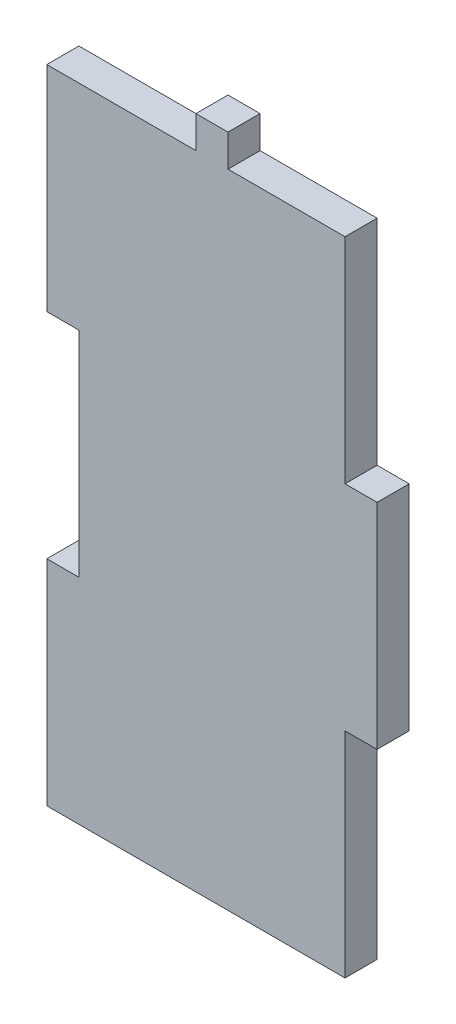
SolidWorks part; units mm, degrees
ref_plane "Front Plane" through (0, 0, 0) normal (0, 0, 1) x (1, 0, 0)
ref_plane "Top Plane" through (0, 0, 0) normal (0, 1, 0) x (1, 0, 0)
ref_plane "Right Plane" through (0, 0, 0) normal (1, 0, 0) x (0, 0, -1)
sketch "Sketch1" plane through (0, 0, 0) normal (0, 0, 1) x (1, 0, 0)
  line L0 (28.57, 0) -> (0, 0)
  line L1 (28.57, 20) -> (28.57, 0)
  line L2 (31.57, 20) -> (28.57, 20)
  line L3 (31.57, 40) -> (31.57, 20)
  line L4 (28.57, 40) -> (31.57, 40)
  line L5 (28.57, 60) -> (28.57, 40)
  line L6 (17.285, 60) -> (28.57, 60)
  line L7 (17.285, 63) -> (17.285, 60)
  line L8 (14.285, 63) -> (17.285, 63)
  line L9 (14.285, 60) -> (14.285, 63)
  line L10 (0, 60) -> (14.285, 60)
  line L11 (0, 40) -> (0, 60)
  line L12 (3, 40) -> (0, 40)
  line L13 (3, 20) -> (3, 40)
  line L14 (0, 20) -> (3, 20)
  line L15 (0, 0) -> (0, 20)
extrude "Plate_thickness_3mm" add sketch "Sketch1" along normal blind 3
sketch "草图1" plane through (0, 0, 3) normal (0, 0, 1) x (1, 0, 0)
  line L0 (0, 0) -> (28.57, 0) construction
  line L1 (0, 60) -> (0.35, 60)
  line L2 (0, 60) -> (0, 0)
  line L3 (0, 0) -> (0.35, 0)
  line L4 (0.35, 60) -> (0.35, 0)
  line L5 (28.57, 20) -> (31.57, 20) construction
  line L6 (3, 40) -> (3.35, 40)
  line L7 (3, 40) -> (3, 20)
  line L8 (3, 20) -> (3.35, 20)
  line L9 (3.35, 40) -> (3.35, 20)
  line L10 (28.57, 60) -> (28.22, 60)
  line L11 (28.57, 60) -> (28.57, 40)
  line L12 (28.57, 40) -> (28.22, 40)
  line L13 (28.22, 60) -> (28.22, 40)
  line L14 (31.57, 40) -> (31.22, 40)
  line L15 (31.57, 40) -> (31.57, 20)
  line L16 (31.57, 20) -> (31.22, 20)
  line L17 (31.22, 40) -> (31.22, 20)
  line L19 (28.57, 20) -> (28.22, 20)
  line L20 (28.57, 20) -> (28.57, 0)
  line L21 (28.57, 0) -> (28.22, 0)
  line L22 (28.22, 20) -> (28.22, 0)
  dimension "D1" = 0.35
  dimension "D2" = 0.35
  dimension "D3" = 0.35
  dimension "D4" = 0.35
  dimension "D5" = 0.35
extrude "切除-拉伸1" cut sketch "草图1" against normal up to surface (3 mm away) up to face at (15.41, 37.875, 0)
